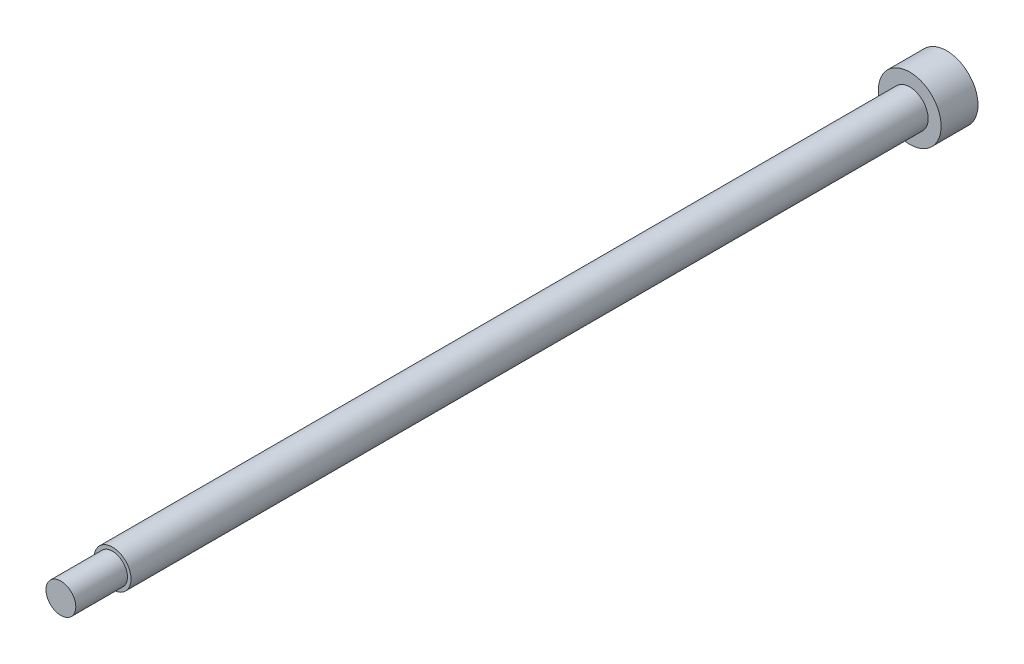
SolidWorks part; units mm, degrees
ref_plane "Front Plane" through (0, 0, 0) normal (0, 0, 1) x (1, 0, 0)
ref_plane "Top Plane" through (0, 0, 0) normal (0, 1, 0) x (1, 0, 0)
ref_plane "Right Plane" through (0, 0, 0) normal (1, 0, 0) x (0, 0, -1)
sketch "Sketch1" plane through (0, 0, 0) normal (0, 0, 1) x (1, 0, 0)
  circle A0 centre (0, 0) radius 2.5
extrude "M5 mounting bolt shank and reduced thread representation" add sketch "Sketch1" along normal blind 108 from offset 7
sketch "Sketch2" plane through (0, 0, 0) normal (0, 0, 1) x (1, 0, 0)
  circle A0 centre (0, 0) radius 2.02
extrude "M5 tap engagement" add sketch "Sketch2" along normal blind 7 from offset 115
sketch "Sketch3" plane through (0, 0, 0) normal (0, 0, 1) x (1, 0, 0)
  circle A0 centre (0, 0) radius 4.25
extrude "Socket cap head" add sketch "Sketch3" along normal blind 5 from offset 2
